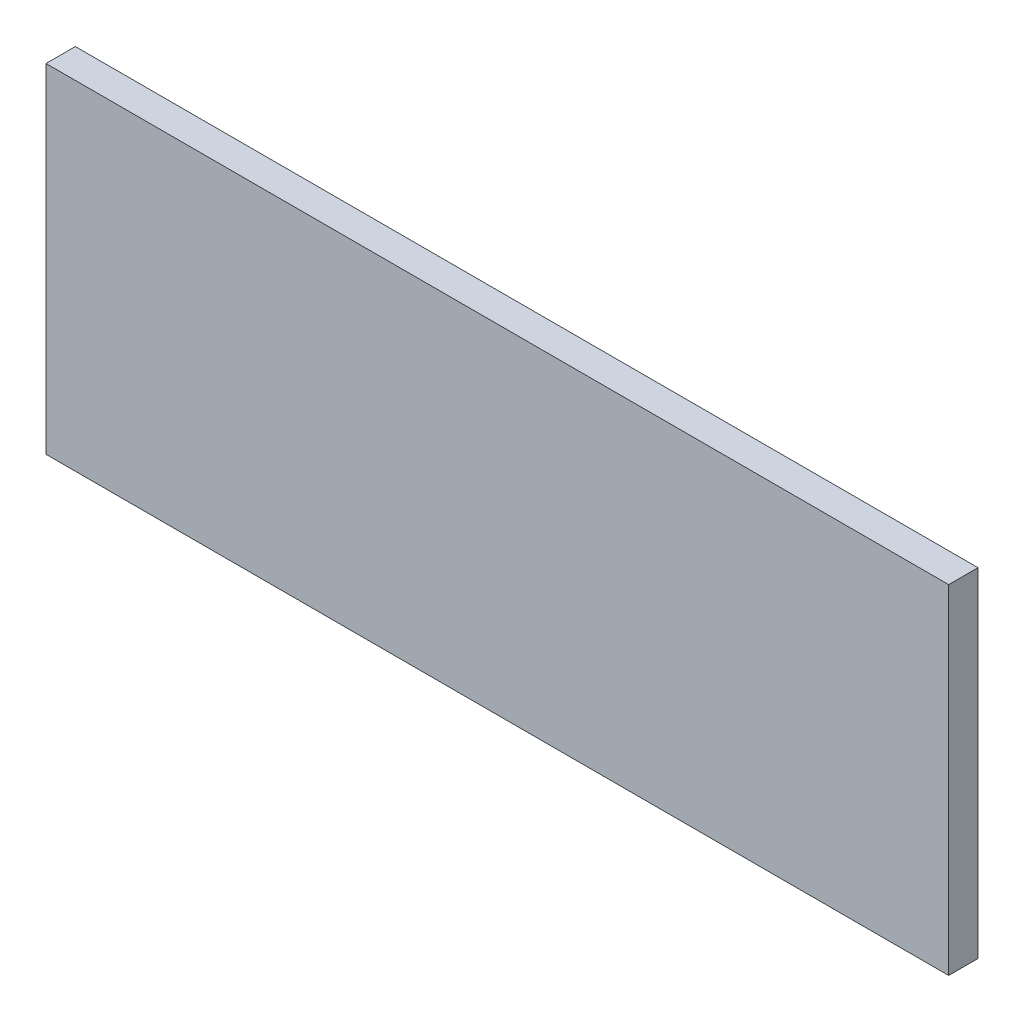
SolidWorks part; units mm, degrees
ref_plane "정면" through (0, 0, 0) normal (0, 0, 1) x (1, 0, 0)
ref_plane "윗면" through (0, 0, 0) normal (0, 1, 0) x (1, 0, 0)
ref_plane "우측면" through (0, 0, 0) normal (1, 0, 0) x (0, 0, -1)
sketch "스케치1" plane through (0, 0, 0) normal (0, 0, 1) x (1, 0, 0)
  line L0 (-190, -65) -> (190, -65)
  line L1 (-200, 75) -> (200, 75)
  line L2 (-200, 75) -> (-200, -75)
  line L3 (-200, -75) -> (200, -75)
  line L4 (200, 75) -> (200, -75)
  line L5 (-200, 75) -> (200, -75) construction
  line L6 (-200, -75) -> (200, 75) construction
  line L7 (190, 65) -> (190, -65)
  line L8 (-190, 65) -> (190, 65)
  line L9 (-190, 65) -> (-190, -65)
  point P0 (0, 0)
  dimension "D1" = 400
  dimension "D2" = 150
  dimension "D3" = 10
extrude "보스-돌출1" add sketch "스케치1" along normal blind 10
sketch "스케치2" plane through (0, 0, 10) normal (0, 0, 1) x (1, 0, 0)
  line L1 (200, -75) -> (-200, -75)
  line L2 (200, -75) -> (200, 75)
  line L3 (200, 75) -> (-200, 75)
  line L4 (-200, -75) -> (-200, 75)
  line L5 (200, -75) -> (-200, 75) construction
  line L6 (200, 75) -> (-200, -75) construction
  point P0 (0, 0)
extrude "보스-돌출2" add sketch "스케치2" along normal blind 3
